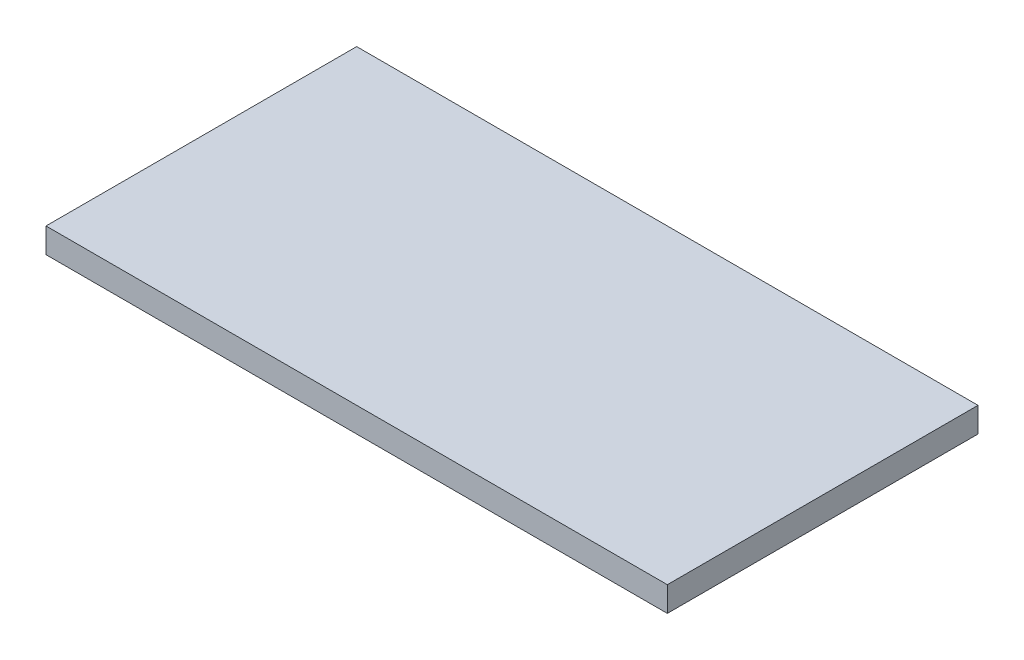
SolidWorks part; units mm, degrees
ref_plane "Front Plane" through (0, 0, 0) normal (0, 0, 1) x (1, 0, 0)
ref_plane "Top Plane" through (0, 0, 0) normal (0, 1, 0) x (1, 0, 0)
ref_plane "Right Plane" through (0, 0, 0) normal (1, 0, 0) x (0, 0, -1)
sketch "Sketch2" plane through (0, 0, 0) normal (0, 1, 0) x (1, 0, 0)
  line L1 (-46.2712, 16.7797) -> (53.7288, 16.7797)
  line L2 (-46.2712, 16.7797) -> (-46.2712, -33.2203)
  line L3 (-46.2712, -33.2203) -> (53.7288, -33.2203)
  line L4 (53.7288, 16.7797) -> (53.7288, -33.2203)
extrude "Boss-Extrude3" add sketch "Sketch2" along normal blind 4.0048
